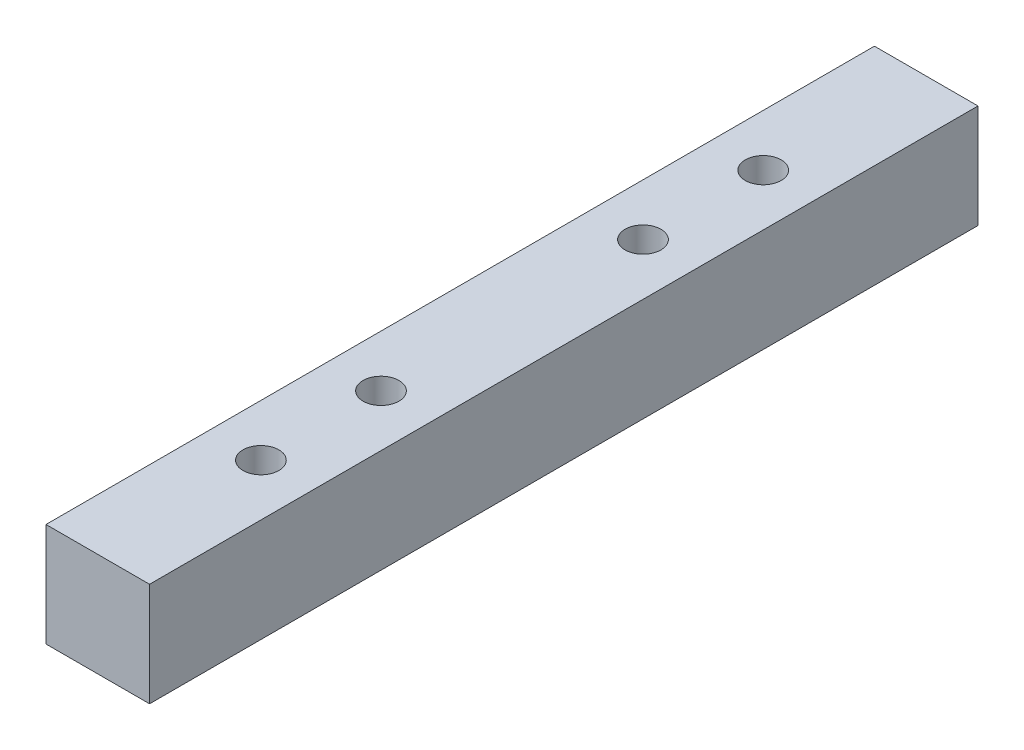
SolidWorks part; units mm, degrees
ref_plane "前视基准面" through (0, 0, 0) normal (0, 0, 1) x (1, 0, 0)
ref_plane "上视基准面" through (0, 0, 0) normal (0, 1, 0) x (1, 0, 0)
ref_plane "右视基准面" through (0, 0, 0) normal (1, 0, 0) x (0, 0, -1)
sketch "草图1" plane through (0, 0, 0) normal (0, 0, 1) x (1, 0, 0)
  line L1 (0, 0) -> (15, 0)
  line L2 (0, 0) -> (0, -15)
  line L3 (0, -15) -> (15, -15)
  line L4 (15, 0) -> (15, -15)
  dimension "D1" = 15
  dimension "D2" = 15
extrude "凸台-拉伸1" add sketch "草图1" along normal blind 120
sketch "草图2" plane through (0, 0, 0) normal (0, 1, 0) x (1, 0, 0)
  line L0 (0, -120) -> (0, 0) construction
  line L1 (0, -60) -> (15, -60) construction
  line L2 (15, -120) -> (15, 0) construction
  line L3 (7.5, -41.025) -> (7.5, -78.975) construction
  circle A0 centre (7.5, -23.61) radius 2.6
  circle A1 centre (7.5, -96.37) radius 2.6
  circle A2 centre (7.5, -41.025) radius 2.6
  circle A3 centre (7.5, -78.975) radius 2.6
  point P16 (7.5, -60)
  dimension "D1" = 5.2
  dimension "D3" = 5.2
  dimension "D7" = 37.95
  dimension "D8" = 5.2
  dimension "D9" = 5.2
  dimension "D2" = 7.5
  dimension "D4" = 7.5
  dimension "D5" = 72.76
  dimension "D6" = 36.39
extrude "切除-拉伸1" cut sketch "草图2" against normal through all
